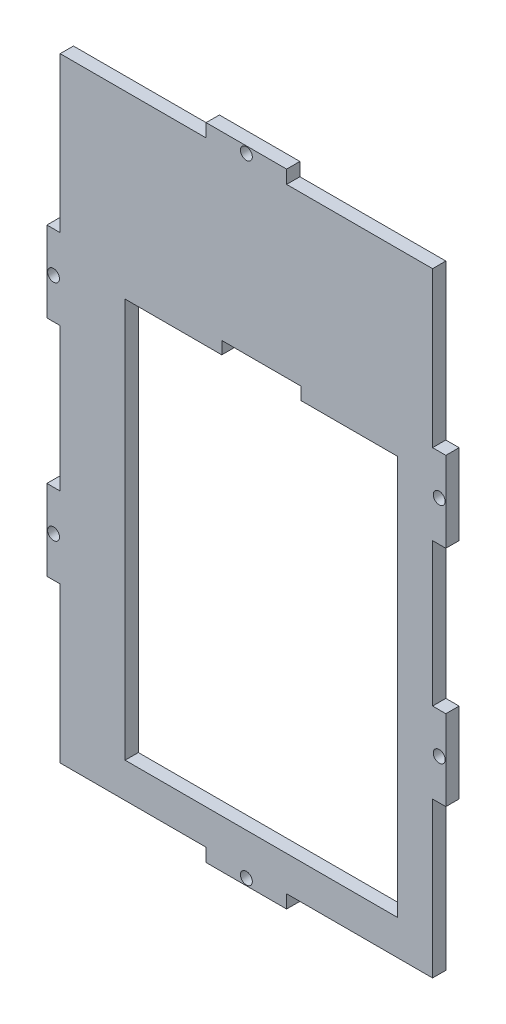
SolidWorks part; units mm, degrees
ref_plane "Front Plane" through (0, 0, 0) normal (0, 0, 1) x (1, 0, 0)
ref_plane "Top Plane" through (0, 0, 0) normal (0, 1, 0) x (1, 0, 0)
ref_plane "Right Plane" through (0, 0, 0) normal (1, 0, 0) x (0, 0, -1)
sketch "Sketch1" plane through (0, 0, 0) normal (0, 0, 1) x (1, 0, 0)
  line L0 (-44.645, 73.645) -> (-14.8817, 73.645)
  line L1 (-44.645, -73.645) -> (44.645, -73.645)
  line L2 (-44.645, -73.645) -> (-44.645, 73.645)
  line L3 (-44.645, 73.645) -> (44.645, 73.645) construction
  line L4 (44.645, -73.645) -> (44.645, 73.645)
  line L5 (-44.645, -73.645) -> (44.645, 73.645) construction
  line L6 (-44.645, 73.645) -> (44.645, -73.645) construction
  line L7 (-14.8817, 73.645) -> (14.8817, 73.645)
  line L8 (14.8817, 73.645) -> (44.645, 73.645)
  point P0 (0, 0)
  dimension "D1" = 89.29
  dimension "D2" = 147.29
extrude "Boss-Extrude1" add sketch "Sketch1" along normal blind 3.18
sketch "Sketch3" plane through (0, 0, 0) normal (0, 0, -1) x (-1, 0, 0)
  line L0 (-36.2767, 30.4733) -> (-36.2767, -65.2767)
  line L1 (-36.2767, -65.2767) -> (29.0733, -65.2767)
  line L2 (29.0733, -65.2767) -> (29.0733, 30.4733)
  line L3 (29.0733, 30.4733) -> (5.8983, 30.4733)
  line L4 (5.8983, 30.4733) -> (5.8983, 33.4733)
  line L5 (5.8983, 33.4733) -> (-13.1017, 33.4733)
  line L6 (-13.1017, 33.4733) -> (-13.1017, 30.4733)
  line L7 (-13.1017, 30.4733) -> (-36.2767, 30.4733)
  line L8 (29.0733, 40.4733) -> (-36.2767, 40.4733)
  line L9 (29.0733, -65.2767) -> (29.0733, 40.4733)
  line L10 (-36.2767, -65.2767) -> (29.0733, -65.2767)
  line L11 (-36.2767, 40.4733) -> (-36.2767, -65.2767)
  line L12 (-36.2767, -65.2767) -> (-36.2767, -73.645) construction
  line L13 (44.645, -73.645) -> (-44.645, -73.645) construction
  line L14 (-36.2767, -65.2767) -> (-44.645, -65.2767) construction
  line L15 (-44.645, -73.645) -> (-44.645, 73.645) construction
  dimension "D1" = 65.35
  dimension "D2" = 95.75
  dimension "D3" = 105.75
  dimension "D4" = 19
  dimension "D5" = 3
extrude "Cut-Extrude1" cut sketch "Sketch3" against normal through all contours L6 L7 L0 L1 L2 L3 L4 L5
sketch "Sketch9" plane through (-44.645, 0, 0) normal (-1, 0, 0) x (0, 0, 1)
  line L0 (0, 0) -> (3.18, 0) construction
  line L1 (0, 73.645) -> (0, -73.645) construction
  line L2 (3.18, 73.645) -> (3.18, -73.645) construction
  line L4 (0, -9.65) -> (3.18, -9.65)
  line L5 (0, -9.65) -> (0, 9.65)
  line L6 (0, 9.65) -> (3.18, 9.65)
  line L7 (3.18, -9.65) -> (3.18, 9.65)
  line L8 (0, -9.65) -> (3.18, 9.65) construction
  line L9 (0, 9.65) -> (3.18, -9.65) construction
  point P6 (1.59, 0)
  dimension "D1" = 19.3
extrude "Boss-Extrude4" [suppressed] add sketch "Sketch9" along normal blind 3.18
sketch "Sketch10" [suppressed] plane through (0, 0, 3.18) normal (0, 0, 1) x (1, 0, 0)
  line L0 (-46.235, 9.65) -> (-46.235, -9.65) construction
  line L1 (-47.825, 9.65) -> (-44.645, 9.65) construction
  line L2 (-47.825, -9.65) -> (-44.645, -9.65) construction
  circle A0 centre (-46.235, 0) radius 1.425
extrude "Cut-Extrude4" [suppressed] cut sketch "Sketch10" against normal through all
mirror "Mirror1" [suppressed] about plane through (0, 0, 0) normal (1, 0, 0)
sketch "Sketch18" plane through (44.645, 0, 0) normal (1, 0, 0) x (0, 0, -1)
  line L0 (0, 0) -> (-3.18, 0) construction
  line L1 (0, -73.645) -> (0, 73.645) construction
  line L2 (-3.18, -73.645) -> (-3.18, 73.645) construction
  line L4 (-3.18, -9.65) -> (0, -9.65)
  line L5 (-3.18, -9.65) -> (-3.18, 9.65)
  line L6 (-3.18, 9.65) -> (0, 9.65)
  line L7 (0, -9.65) -> (0, 9.65)
  line L8 (-3.18, -9.65) -> (0, 9.65) construction
  line L9 (-3.18, 9.65) -> (0, -9.65) construction
  point P6 (-1.59, 0)
  dimension "D1" = 19.3
extrude "Boss-Extrude8" [suppressed] add sketch "Sketch18" along normal blind 3.18
sketch "Sketch19" [suppressed] plane through (0, 0, 3.18) normal (0, 0, 1) x (1, 0, 0)
  line L0 (46.235, -9.65) -> (46.235, 9.65) construction
  line L1 (47.825, -9.65) -> (44.645, -9.65) construction
  line L2 (47.825, 9.65) -> (44.645, 9.65) construction
  circle A0 centre (46.235, 0) radius 1.425
extrude "Cut-Extrude8" [suppressed] cut sketch "Sketch19" against normal through all
mirror "Mirror2" [suppressed] about plane through (0, 0, 0) normal (1, 0, 0)
sketch "Sketch20" plane through (0, 0, 3.18) normal (0, 0, 1) x (1, 0, 0)
  line L0 (0, 70.465) -> (0, 0) construction
  line L1 (44.645, 73.645) -> (-44.645, 73.645) construction
  line L2 (-9.65, 73.645) -> (9.65, 73.645)
  line L3 (9.65, 73.645) -> (9.65, 70.465)
  line L4 (9.65, 70.465) -> (1.425, 70.465)
  line L5 (1.425, 70.465) -> (1.425, 62.665)
  line L6 (1.425, 62.665) -> (3.175, 62.665)
  line L7 (3.175, 62.665) -> (3.175, 60.285)
  line L8 (3.175, 60.285) -> (1.425, 60.285)
  line L9 (1.425, 60.285) -> (1.425, 54.665)
  line L10 (1.425, 54.665) -> (-1.425, 54.665)
  line L11 (-1.425, 54.665) -> (-1.425, 60.285)
  line L12 (-1.425, 60.285) -> (-3.175, 60.285)
  line L13 (-3.175, 60.285) -> (-3.175, 62.665)
  line L14 (-3.175, 62.665) -> (-1.425, 62.665)
  line L15 (-1.425, 62.665) -> (-1.425, 70.465)
  line L16 (-1.425, 70.465) -> (-9.65, 70.465)
  line L17 (-9.65, 70.465) -> (-9.65, 73.645)
  dimension "D1" = 19.3
  dimension "D2" = 3.18
  dimension "D3" = 15.8
  dimension "D4" = 6.35
  dimension "D5" = 2.38
  dimension "D6" = 2.85
  dimension "D7" = 7.8
extrude "Cut-Extrude9" [suppressed] cut sketch "Sketch20" against normal through all
mirror "Mirror3" [suppressed] about plane through (0, 0, 0) normal (0, 1, 0)
sketch "Sketch23" plane through (0, 0, 3.18) normal (0, 0, 1) x (1, 0, 0)
  line L0 (-44.645, 13.995) -> (-44.645, 33.295)
  line L1 (-44.645, 73.645) -> (-44.645, -73.645) construction
  line L2 (-44.645, 33.295) -> (-41.465, 33.295)
  line L3 (-41.465, 33.295) -> (-41.465, 25.07)
  line L4 (-41.465, 25.07) -> (-33.665, 25.07)
  line L5 (-33.665, 25.07) -> (-33.665, 26.82)
  line L6 (-33.665, 26.82) -> (-31.285, 26.82)
  line L7 (-31.285, 26.82) -> (-31.285, 25.07)
  line L8 (-31.285, 25.07) -> (-25.665, 25.07)
  line L9 (-25.665, 25.07) -> (-25.665, 22.22)
  line L10 (-25.665, 22.22) -> (-31.285, 22.22)
  line L11 (-31.285, 22.22) -> (-31.285, 20.47)
  line L12 (-31.285, 20.47) -> (-33.665, 20.47)
  line L13 (-33.665, 20.47) -> (-33.665, 22.22)
  line L14 (-33.665, 22.22) -> (-41.465, 22.22)
  line L15 (-41.465, 22.22) -> (-41.465, 13.995)
  line L16 (-41.465, 13.995) -> (-44.645, 13.995)
  line L17 (44.645, 73.645) -> (-44.645, 73.645) construction
  line L19 (-25.665, 23.645) -> (-44.645, 23.645) construction
  line L20 (-44.645, -33.295) -> (-44.645, -13.995)
  line L21 (-44.645, -13.995) -> (-41.465, -13.995)
  line L22 (-41.465, -13.995) -> (-41.465, -22.22)
  line L23 (-41.465, -22.22) -> (-33.665, -22.22)
  line L24 (-33.665, -22.22) -> (-33.665, -20.47)
  line L25 (-33.665, -20.47) -> (-31.285, -20.47)
  line L26 (-31.285, -20.47) -> (-31.285, -22.22)
  line L27 (-31.285, -22.22) -> (-25.665, -22.22)
  line L28 (-25.665, -22.22) -> (-25.665, -25.07)
  line L29 (-25.665, -25.07) -> (-31.285, -25.07)
  line L30 (-31.285, -25.07) -> (-31.285, -26.82)
  line L31 (-31.285, -26.82) -> (-33.665, -26.82)
  line L32 (-33.665, -26.82) -> (-33.665, -25.07)
  line L33 (-33.665, -25.07) -> (-41.465, -25.07)
  line L34 (-41.465, -25.07) -> (-41.465, -33.295)
  line L35 (-41.465, -33.295) -> (-44.645, -33.295)
  line L36 (-44.645, -23.645) -> (-25.665, -23.645) construction
  line L37 (-44.645, -73.645) -> (44.645, -73.645) construction
  dimension "D1" = 50
  dimension "D2" = 19.3
  dimension "D3" = 3.18
  dimension "D4" = 15.8
  dimension "D5" = 6.35
  dimension "D6" = 2.85
  dimension "D7" = 7.8
  dimension "D8" = 2.38
  dimension "D9" = 19.3
  dimension "D10" = 3.18
  dimension "D11" = 7.8
  dimension "D12" = 15.8
  dimension "D13" = 6.35
  dimension "D14" = 2.85
  dimension "D15" = 2.38
  dimension "D16" = 50
  dimension "D17" = 1.75
extrude "Cut-Extrude10" [suppressed] cut sketch "Sketch23" against normal through all
sketch "Sketch24" plane through (0, 0, 3.18) normal (0, 0, 1) x (1, 0, 0)
  line L0 (44.645, -13.995) -> (44.645, -33.295)
  line L1 (44.645, -73.645) -> (44.645, 73.645) construction
  line L2 (44.645, -33.295) -> (41.465, -33.295)
  line L3 (41.465, -33.295) -> (41.465, -25.07)
  line L4 (41.465, -25.07) -> (33.665, -25.07)
  line L5 (33.665, -25.07) -> (33.665, -26.82)
  line L6 (33.665, -26.82) -> (31.285, -26.82)
  line L7 (31.285, -26.82) -> (31.285, -25.07)
  line L8 (31.285, -25.07) -> (25.665, -25.07)
  line L9 (25.665, -25.07) -> (25.665, -22.22)
  line L10 (25.665, -22.22) -> (31.285, -22.22)
  line L11 (31.285, -22.22) -> (31.285, -20.47)
  line L12 (31.285, -20.47) -> (33.665, -20.47)
  line L13 (33.665, -20.47) -> (33.665, -22.22)
  line L14 (33.665, -22.22) -> (41.465, -22.22)
  line L15 (41.465, -22.22) -> (41.465, -13.995)
  line L16 (41.465, -13.995) -> (44.645, -13.995)
  line L17 (25.665, -23.645) -> (44.645, -23.645) construction
  line L18 (-44.645, -73.645) -> (44.645, -73.645) construction
  line L19 (44.645, 33.295) -> (44.645, 13.995)
  line L20 (44.645, 13.995) -> (41.465, 13.995)
  line L21 (41.465, 13.995) -> (41.465, 22.22)
  line L22 (41.465, 22.22) -> (33.665, 22.22)
  line L23 (33.665, 22.22) -> (33.665, 20.47)
  line L24 (33.665, 20.47) -> (31.285, 20.47)
  line L25 (31.285, 20.47) -> (31.285, 22.22)
  line L26 (31.285, 22.22) -> (25.665, 22.22)
  line L27 (25.665, 22.22) -> (25.665, 25.07)
  line L28 (25.665, 25.07) -> (31.285, 25.07)
  line L29 (31.285, 25.07) -> (31.285, 26.82)
  line L30 (31.285, 26.82) -> (33.665, 26.82)
  line L31 (33.665, 26.82) -> (33.665, 25.07)
  line L32 (33.665, 25.07) -> (41.465, 25.07)
  line L33 (41.465, 25.07) -> (41.465, 33.295)
  line L34 (41.465, 33.295) -> (44.645, 33.295)
  line L35 (25.665, 23.645) -> (44.645, 23.645) construction
  line L36 (44.645, 73.645) -> (-44.645, 73.645) construction
  dimension "D1" = 19.3
  dimension "D2" = 3.18
  dimension "D3" = 15.8
  dimension "D4" = 7.8
  dimension "D5" = 6.35
  dimension "D6" = 2.85
  dimension "D7" = 2.38
  dimension "D8" = 50
  dimension "D9" = 19.3
  dimension "D10" = 3.18
  dimension "D11" = 7.8
  dimension "D12" = 15.8
  dimension "D13" = 6.35
  dimension "D14" = 2.85
  dimension "D15" = 2.38
  dimension "D16" = 50
extrude "Cut-Extrude11" [suppressed] cut sketch "Sketch24" against normal through all
sketch "Sketch25" plane through (0, 0, 3.18) normal (0, 0, 1) x (1, 0, 0)
  line L0 (9.65, -73.645) -> (-9.65, -73.645)
  line L1 (-44.645, -73.645) -> (44.645, -73.645) construction
  line L2 (-9.65, -73.645) -> (-9.65, -70.465)
  line L3 (-9.65, -70.465) -> (-1.425, -70.465)
  line L4 (-1.425, -70.465) -> (-1.425, -62.665)
  line L5 (-1.425, -62.665) -> (-3.175, -62.665)
  line L6 (-3.175, -62.665) -> (-3.175, -60.285)
  line L7 (-3.175, -60.285) -> (-1.425, -60.285)
  line L8 (-1.425, -60.285) -> (-1.425, -54.665)
  line L9 (-1.425, -54.665) -> (1.425, -54.665)
  line L10 (1.425, -54.665) -> (1.425, -60.285)
  line L11 (1.425, -60.285) -> (3.175, -60.285)
  line L12 (3.175, -60.285) -> (3.175, -62.665)
  line L13 (3.175, -62.665) -> (1.425, -62.665)
  line L14 (1.425, -62.665) -> (1.425, -70.465)
  line L15 (1.425, -70.465) -> (9.65, -70.465)
  line L16 (9.65, -70.465) -> (9.65, -73.645)
  line L17 (0, -73.645) -> (0, 0) construction
  dimension "D1" = 19.3
  dimension "D2" = 3.18
  dimension "D3" = 15.8
  dimension "D4" = 7.8
  dimension "D5" = 6.35
  dimension "D6" = 2.85
  dimension "D7" = 2.38
extrude "Cut-Extrude12" [suppressed] cut sketch "Sketch25" against normal through all
sketch "Sketch26" plane through (0, 0, 3.18) normal (0, 0, 1) x (1, 0, 0)
  line L0 (-9.65, 73.645) -> (9.65, 73.645)
  line L1 (44.645, 73.645) -> (-44.645, 73.645) construction
  line L2 (9.65, 73.645) -> (9.65, 70.465)
  line L3 (9.65, 70.465) -> (1.425, 70.465)
  line L4 (1.425, 70.465) -> (1.425, 62.665)
  line L5 (1.425, 62.665) -> (3.175, 62.665)
  line L6 (3.175, 62.665) -> (3.175, 60.285)
  line L7 (3.175, 60.285) -> (1.425, 60.285)
  line L8 (1.425, 60.285) -> (1.425, 54.665)
  line L9 (1.425, 54.665) -> (-1.425, 54.665)
  line L10 (-1.425, 54.665) -> (-1.425, 60.285)
  line L11 (-1.425, 60.285) -> (-3.175, 60.285)
  line L12 (-3.175, 60.285) -> (-3.175, 62.665)
  line L13 (-3.175, 62.665) -> (-1.425, 62.665)
  line L14 (-1.425, 62.665) -> (-1.425, 70.465)
  line L15 (-1.425, 70.465) -> (-9.65, 70.465)
  line L16 (-9.65, 70.465) -> (-9.65, 73.645)
  line L17 (0, 73.645) -> (0, -4.4192) construction
  dimension "D1" = 19.3
  dimension "D2" = 3.18
  dimension "D3" = 7.8
  dimension "D4" = 15.8
  dimension "D5" = 6.35
  dimension "D6" = 2.85
  dimension "D7" = 2.38
extrude "Cut-Extrude13" [suppressed] cut sketch "Sketch26" against normal through all
mirror "Mirror4" [suppressed] about plane through (0, 0, 0) normal (1, 0, 0)
mirror "Mirror5" [suppressed] about plane through (0, 0, 0) normal (1, 0, 0)
mirror "Mirror6" [suppressed] about plane through (0, 0, 0) normal (0, 1, 0)
mirror "Mirror7" [suppressed] about plane through (0, 0, 0) normal (0, 1, 0)
sketch "Sketch27" plane through (-44.645, 0, 0) normal (-1, 0, 0) x (0, 0, 1)
  line L0 (0, -36.475) -> (0, -17.175)
  line L1 (0, 73.645) -> (0, -73.645) construction
  line L2 (0, -17.175) -> (3.18, -17.175)
  line L3 (3.18, 73.645) -> (3.18, -73.645) construction
  line L4 (3.18, -17.175) -> (3.18, -36.475)
  line L5 (3.18, -36.475) -> (0, -36.475)
  line L6 (3.18, -26.825) -> (0, -26.825) construction
  line L7 (3.18, -73.645) -> (0, -73.645) construction
  dimension "D1" = 19.3
  dimension "D2" = 46.82
extrude "Boss-Extrude9" add sketch "Sketch27" along normal blind 3.18
sketch "Sketch28" plane through (0, -73.645, 0) normal (0, -1, 0) x (1, 0, 0)
  line L0 (9.65, 0) -> (-9.65, 0)
  line L1 (-44.645, 0) -> (44.645, 0) construction
  line L2 (-9.65, 0) -> (-9.65, 3.18)
  line L3 (-44.645, 3.18) -> (44.645, 3.18) construction
  line L4 (-9.65, 3.18) -> (9.65, 3.18)
  line L5 (9.65, 3.18) -> (9.65, 0)
  line L6 (0, 0) -> (0, 3.18) construction
  dimension "D1" = 19.3
extrude "Boss-Extrude10" add sketch "Sketch28" along normal blind 3.18
sketch "Sketch29" plane through (0, 0, 3.18) normal (0, 0, 1) x (1, 0, 0)
  line L0 (-47.825, -26.825) -> (-37.3062, -26.825) construction
  line L1 (-47.825, -36.475) -> (-47.825, -17.175) construction
  line L2 (-46.235, -17.175) -> (-46.235, -36.475) construction
  line L3 (-47.825, -17.175) -> (-44.645, -17.175) construction
  line L4 (-47.825, -36.475) -> (-44.645, -36.475) construction
  circle A0 centre (-46.235, -26.825) radius 1.425
extrude "Cut-Extrude14" cut sketch "Sketch29" against normal through all
sketch "Sketch30" plane through (0, 0, 3.18) normal (0, 0, 1) x (1, 0, 0)
  line L0 (0, -76.825) -> (0, -66.2855) construction
  line L1 (9.65, -76.825) -> (-9.65, -76.825) construction
  line L2 (9.65, -75.235) -> (-9.65, -75.235) construction
  line L3 (9.65, -76.825) -> (9.65, -73.645) construction
  line L4 (-9.65, -76.825) -> (-9.65, -73.645) construction
  circle A0 centre (0, -75.235) radius 1.425
extrude "Cut-Extrude15" cut sketch "Sketch30" against normal through all
mirror "Mirror8" about plane through (0, 0, 0) normal (1, 0, 0) of "Cut-Extrude14", "Boss-Extrude9"
mirror "Mirror9" about plane through (0, 0, 0) normal (0, 1, 0) of "Cut-Extrude15", "Boss-Extrude10", "Mirror8", "Boss-Extrude9", "Cut-Extrude14"
